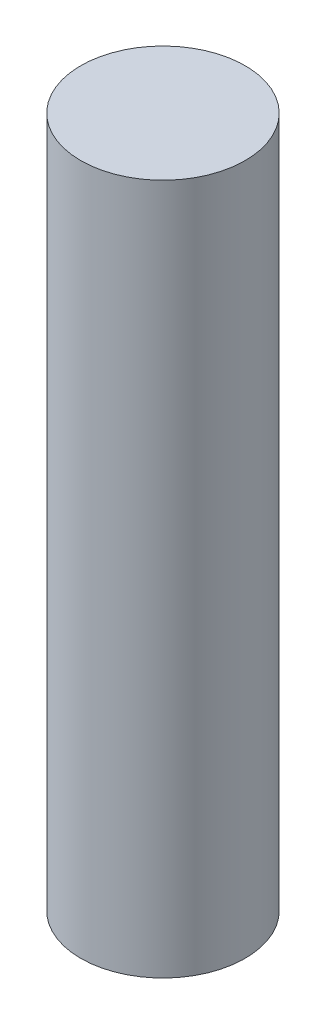
SolidWorks part; units mm, degrees
ref_plane "Front Plane" through (0, 0, 0) normal (0, 0, 1) x (1, 0, 0)
ref_plane "Top Plane" through (0, 0, 0) normal (0, 1, 0) x (1, 0, 0)
ref_plane "Right Plane" through (0, 0, 0) normal (1, 0, 0) x (0, 0, -1)
sketch "Sketch1" plane through (0, 0, 0) normal (0, 1, 0) x (1, 0, 0)
  circle A0 centre (0, 0) radius 11.9
extrude "Boss-Extrude1" add sketch "Sketch1" along normal blind 100
